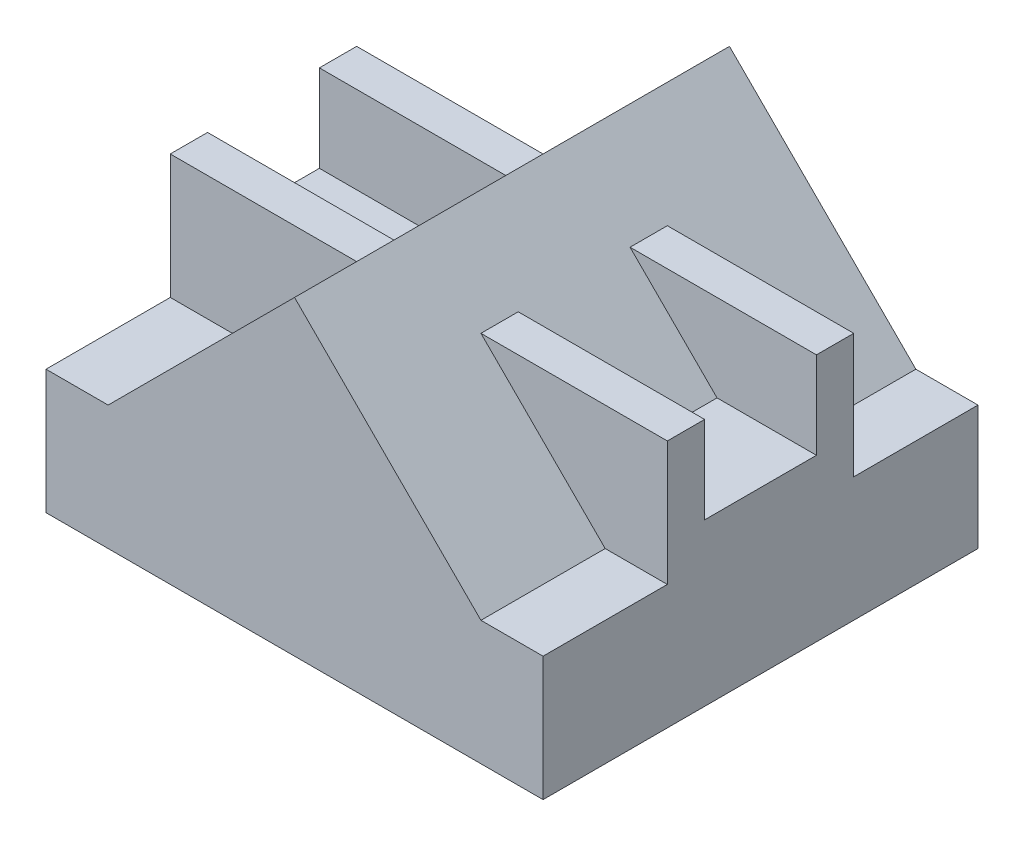
SolidWorks part; units mm, degrees
ref_plane "Front Plane" through (0, 0, 0) normal (0, 0, 1) x (1, 0, 0)
ref_plane "Top Plane" through (0, 0, 0) normal (0, 1, 0) x (1, 0, 0)
ref_plane "Right Plane" through (0, 0, 0) normal (1, 0, 0) x (0, 0, -1)
sketch "Sketch1" plane through (0, 0, 0) normal (0, 0, 1) x (1, 0, 0)
  line L0 (100, 0) -> (-100, 0)
  line L1 (-100, 0) -> (-100, 50)
  line L2 (0, 0) -> (0, 125)
  line L3 (0, 125) -> (-75, 50)
  line L4 (-100, 50) -> (-75, 50)
  line L5 (100, 0) -> (100, 50)
  line L6 (100, 50) -> (75, 50)
  line L7 (0, 125) -> (75, 50)
  dimension "D1" = 45
  dimension "D2" = 125
  dimension "D3" = 50
extrude "Boss-Extrude1" add sketch "Sketch1" against normal blind 175 contours L7 L2 L0 L5 L6 | L4 L1 L0 L2 L3
sketch "Sketch2" plane through (100, 0, 0) normal (1, 0, 0) x (0, 0, -1)
  line L0 (0, 50) -> (0, 0)
  line L1 (0, 0) -> (175, 0)
  line L2 (175, 0) -> (175, 50)
  line L3 (175, 50) -> (125, 50)
  line L4 (175, 50) -> (0, 50) construction
  line L5 (125, 50) -> (125, 100)
  line L6 (125, 100) -> (110, 100)
  line L7 (110, 100) -> (110, 65)
  line L8 (0, 50) -> (50, 50)
  line L9 (175, 50) -> (0, 50) construction
  line L10 (50, 50) -> (50, 100)
  line L11 (50, 100) -> (65, 100)
  line L12 (65, 100) -> (65, 65)
  line L13 (65, 65) -> (110, 65)
  dimension "D1" = 100
extrude "Boss-Extrude2" add sketch "Sketch2" against normal blind 200
